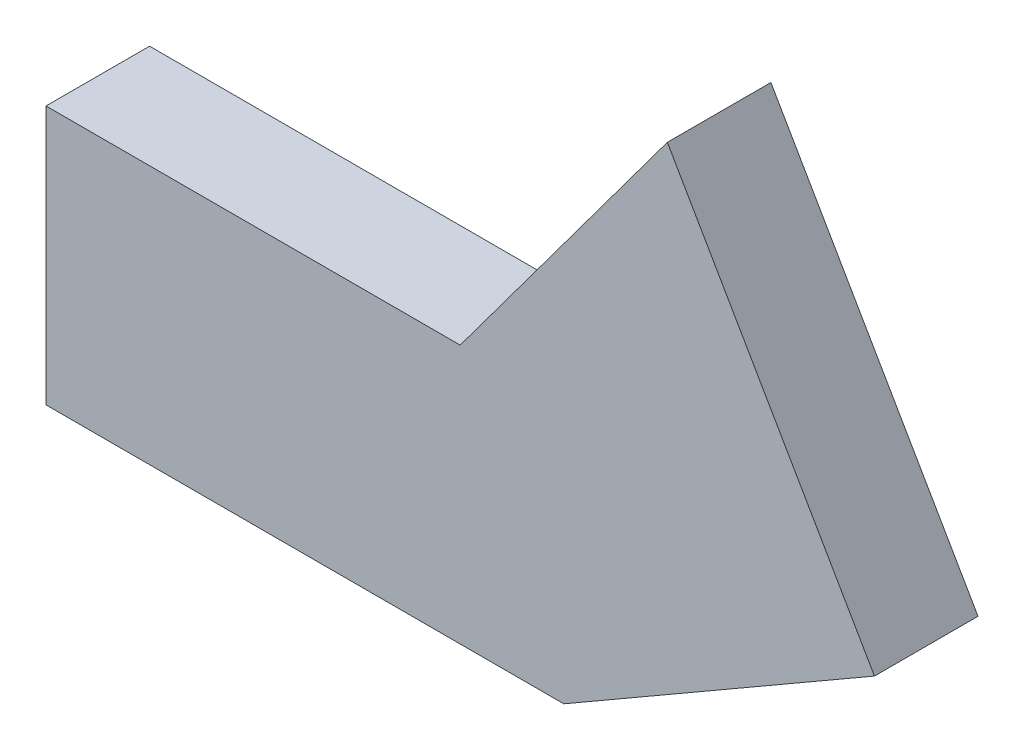
SolidWorks part; units mm, degrees
ref_plane "Front" through (0, 0, 0) normal (0, 0, 1) x (1, 0, 0)
ref_plane "Top" through (0, 0, 0) normal (0, 1, 0) x (1, 0, 0)
ref_plane "Right" through (0, 0, 0) normal (1, 0, 0) x (0, 0, -1)
sketch "Sketch2" plane through (0, 0, 0) normal (0, 0, 1) x (1, 0, 0)
  line L0 (0, 0) -> (100, 0)
  line L1 (100, 0) -> (160, 34.641)
  line L2 (160, 34.641) -> (120, 103.923)
  line L3 (120, 103.923) -> (80, 50)
  line L4 (80, 50) -> (0, 50)
  line L5 (0, 50) -> (0, 0)
  dimension "D1" = 50
  dimension "D2" = 100
  dimension "D3" = 80
  dimension "D4" = 80
  dimension "D5" = 160
  dimension "D6" = 150
extrude "Boss-Extrude1" add sketch "Sketch2" along normal blind 20
